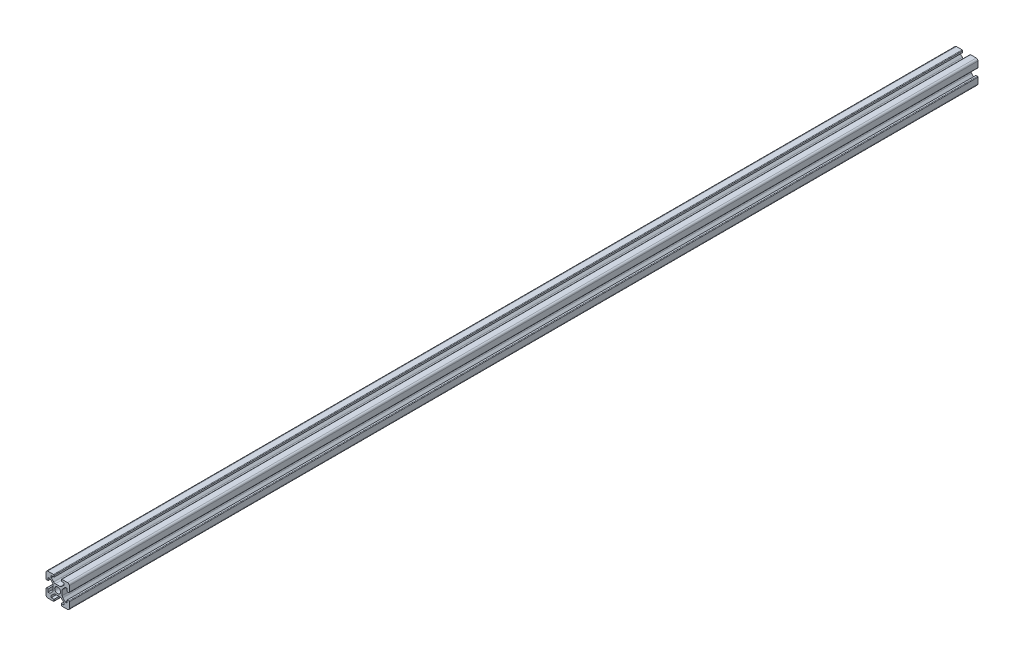
SolidWorks part; units mm, degrees
ref_plane "前视基准面" through (0, 0, 0) normal (0, 0, 1) x (1, 0, 0)
ref_plane "上视基准面" through (0, 0, 0) normal (0, 1, 0) x (1, 0, 0)
ref_plane "右视基准面" through (0, 0, 0) normal (1, 0, 0) x (0, 0, -1)
sketch "草图1" plane through (0, 0, 0) normal (0, 0, 1) x (1, 0, 0)
  line L0 (-19.2539, 0) -> (18.8323, 0) construction
  line L1 (0, 18.4429) -> (0, -19.8143) construction
  line L2 (3.9, 0) -> (3.9, 1.9716)
  line L3 (-8.5, 10) -> (-3.6, 10)
  line L4 (-10, 8.5) -> (-10, 3.6)
  line L5 (-8.5, -10) -> (-3.6, -10)
  line L6 (10, 8.5) -> (10, 3.6)
  line L7 (-10, 10) -> (10, -10) construction
  line L8 (-10, -10) -> (10, 10) construction
  line L9 (4.4858, 3.3858) -> (6.6, 5.5)
  line L10 (6.6, 5.5) -> (8.2, 5.5)
  line L11 (8.2, 5.5) -> (8.2, 3.1)
  line L12 (8.2, 3.1) -> (9.5, 3.1)
  line L17 (8.2, -3.1) -> (9.5, -3.1)
  line L18 (8.2, -5.5) -> (8.2, -3.1)
  line L19 (6.6, -5.5) -> (8.2, -5.5)
  line L20 (4.4858, -3.3858) -> (6.6, -5.5)
  line L21 (3.9, 0) -> (3.9, -1.9716)
  line L22 (10, -3.6) -> (10, -8.5)
  line L23 (-3.1, 8.2) -> (-3.1, 9.5)
  line L24 (-5.5, 8.2) -> (-3.1, 8.2)
  line L25 (-5.5, 6.6) -> (-5.5, 8.2)
  line L26 (-3.3858, 4.4858) -> (-5.5, 6.6)
  line L27 (0, 3.9) -> (-1.9716, 3.9)
  line L28 (0, 3.9) -> (1.9716, 3.9)
  line L29 (3.3858, 4.4858) -> (5.5, 6.6)
  line L30 (5.5, 6.6) -> (5.5, 8.2)
  line L31 (5.5, 8.2) -> (3.1, 8.2)
  line L32 (3.1, 8.2) -> (3.1, 9.5)
  line L33 (3.6, 10) -> (8.5, 10)
  line L34 (-8.2, -3.1) -> (-9.5, -3.1)
  line L35 (-8.2, -5.5) -> (-8.2, -3.1)
  line L36 (-6.6, -5.5) -> (-8.2, -5.5)
  line L37 (-4.4858, -3.3858) -> (-6.6, -5.5)
  line L38 (-3.9, 0) -> (-3.9, -1.9716)
  line L39 (-3.9, 0) -> (-3.9, 1.9716)
  line L40 (-4.4858, 3.3858) -> (-6.6, 5.5)
  line L41 (-6.6, 5.5) -> (-8.2, 5.5)
  line L42 (-8.2, 5.5) -> (-8.2, 3.1)
  line L43 (-8.2, 3.1) -> (-9.5, 3.1)
  line L44 (3.1, -8.2) -> (3.1, -9.5)
  line L45 (5.5, -8.2) -> (3.1, -8.2)
  line L46 (5.5, -6.6) -> (5.5, -8.2)
  line L47 (3.3858, -4.4858) -> (5.5, -6.6)
  line L48 (0, -3.9) -> (1.9716, -3.9)
  line L49 (0, -3.9) -> (-1.9716, -3.9)
  line L50 (-3.3858, -4.4858) -> (-5.5, -6.6)
  line L51 (-5.5, -6.6) -> (-5.5, -8.2)
  line L52 (-5.5, -8.2) -> (-3.1, -8.2)
  line L53 (-3.1, -8.2) -> (-3.1, -9.5)
  line L54 (3.6, -10) -> (8.5, -10)
  line L55 (-10, -3.6) -> (-10, -8.5)
  circle A0 centre (0, 0) radius 2.5
  arc A1 (3.9, 1.9716) -> (4.4858, 3.3858) centre (5.9, 1.9716) cw
  arc A2 (4.4858, -3.3858) -> (3.9, -1.9716) centre (5.9, -1.9716) cw
  arc A5 (10, 8.5) -> (8.5, 10) centre (8.5, 8.5) ccw
  arc A6 (-10, 8.5) -> (-8.5, 10) centre (-8.5, 8.5) cw
  arc A7 (-8.5, -10) -> (-10, -8.5) centre (-8.5, -8.5) cw
  arc A8 (10, -8.5) -> (8.5, -10) centre (8.5, -8.5) cw
  arc A9 (9.5, 3.1) -> (10, 3.6) centre (9.5, 3.6) ccw
  arc A10 (10, -3.6) -> (9.5, -3.1) centre (9.5, -3.6) ccw
  arc A11 (-3.6, 10) -> (-3.1, 9.5) centre (-3.6, 9.5) cw
  arc A12 (-3.3858, 4.4858) -> (-1.9716, 3.9) centre (-1.9716, 5.9) ccw
  arc A13 (1.9716, 3.9) -> (3.3858, 4.4858) centre (1.9716, 5.9) ccw
  arc A14 (3.1, 9.5) -> (3.6, 10) centre (3.6, 9.5) cw
  arc A15 (-10, -3.6) -> (-9.5, -3.1) centre (-9.5, -3.6) cw
  arc A16 (-4.4858, -3.3858) -> (-3.9, -1.9716) centre (-5.9, -1.9716) ccw
  arc A17 (-3.9, 1.9716) -> (-4.4858, 3.3858) centre (-5.9, 1.9716) ccw
  arc A18 (-9.5, 3.1) -> (-10, 3.6) centre (-9.5, 3.6) cw
  arc A19 (3.6, -10) -> (3.1, -9.5) centre (3.6, -9.5) cw
  arc A20 (3.3858, -4.4858) -> (1.9716, -3.9) centre (1.9716, -5.9) ccw
  arc A21 (-1.9716, -3.9) -> (-3.3858, -4.4858) centre (-1.9716, -5.9) ccw
  arc A22 (-3.1, -9.5) -> (-3.6, -10) centre (-3.6, -9.5) cw
  point P34 (3.9, 2.8)
  point P37 (3.9, -2.8)
  point P42 (10, 3.1)
  point P53 (10, -3.1)
  dimension "D1" = 5
  dimension "D10" = 2
  dimension "D13" = 1.5
  dimension "D8" = 0.5
  dimension "D3" = 6.1
  dimension "D4" = 11
  dimension "D5" = 6.2
  dimension "D6" = 1.8
  dimension "D7" = 3.4
  dimension "D16" = 20
extrude "凸台-拉伸1" add sketch "草图1" along normal blind 780
